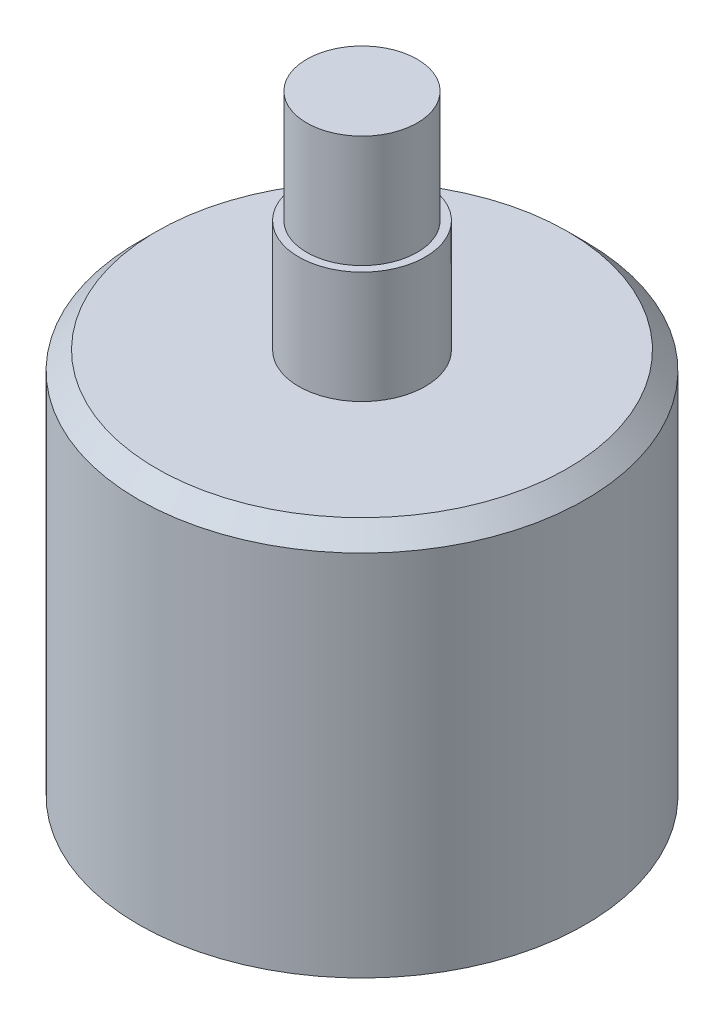
SolidWorks part; units mm, degrees
ref_plane "Front Plane" through (0, 0, 0) normal (0, 0, 1) x (1, 0, 0)
ref_plane "Top Plane" through (0, 0, 0) normal (0, 1, 0) x (1, 0, 0)
ref_plane "Right Plane" through (0, 0, 0) normal (1, 0, 0) x (0, 0, -1)
sketch "Sketch1" plane through (0, 0, 0) normal (0, 0, 1) x (1, 0, 0)
  line L0 (0, 0) -> (0, 35123.5242) construction
  line L1 (0, 40.7) -> (3.45, 40.7)
  line L2 (3.45, 40.7) -> (3.45, 33.7)
  line L3 (3.45, 33.7) -> (3.95, 33.7)
  line L4 (3.95, 33.7) -> (3.95, 26.7)
  line L5 (3.95, 26.7) -> (12.8275, 26.7)
  line L6 (12.8275, 26.7) -> (13.95, 25.5775)
  line L7 (13.95, 25.5775) -> (13.95, 2.6)
  line L8 (13.95, 2.6) -> (3, 2.6)
  line L9 (3, 2.6) -> (3, 0)
  line L10 (3, 0) -> (0, 0)
  line L11 (0, 40.7) -> (0, 0)
  dimension "D1" = 3.45
  dimension "D2" = 3.95
  dimension "D3" = 7
  dimension "D4" = 14
  dimension "D5" = 24.1
  dimension "D6" = 3
  dimension "D7" = 40.7
  dimension "D8" = 1.5875
  dimension "D9" = 135
  dimension "D10" = 13.95
revolve "Revolve1" add sketch "Sketch1" angle 360 about L0
sketch "Sketch2" plane through (0, 2.6, 0) normal (0, -1, 0) x (1, 0, 0)
  line L0 (0, 8) -> (0, -8) construction
  line L1 (-9.5, 0) -> (9.5, 0) construction
  circle A0 centre (-9.5, 0) radius 1.2573
  circle A1 centre (0, -8) radius 1.2573
  circle A2 centre (9.5, 0) radius 1.2573
  circle A3 centre (0, 8) radius 1.2573
  point P2 (0, 0)
  point P6 (0, 0)
  dimension "D4" = 2.5146
  dimension "D1" = 90
  dimension "D2" = 16
  dimension "D3" = 19
extrude "Cut-Extrude1" cut sketch "Sketch2" against normal blind 3.175
